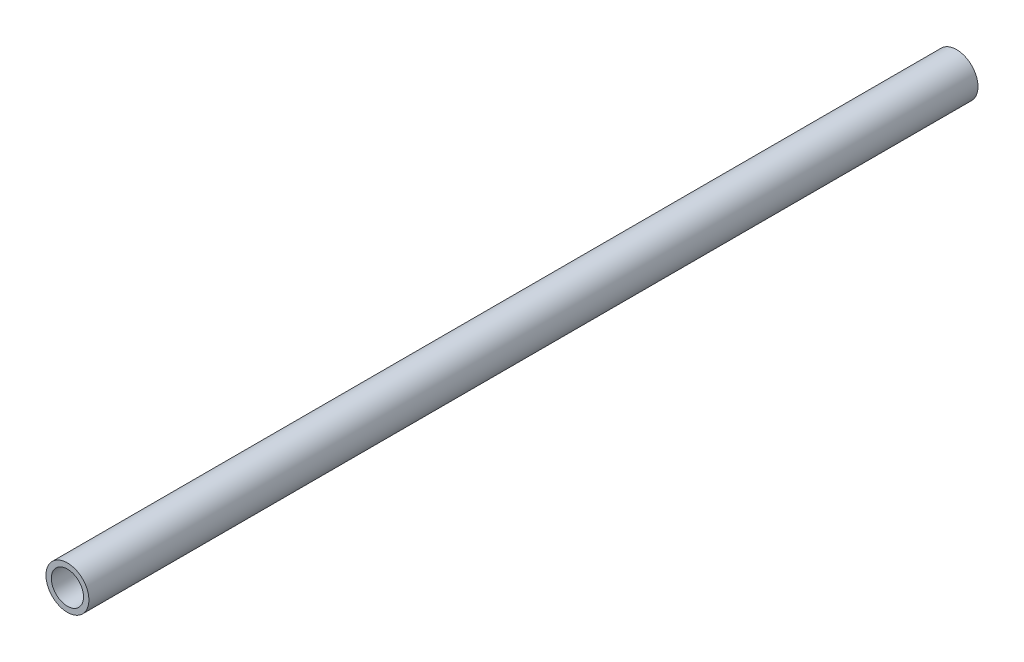
SolidWorks part; units mm, degrees
material "PC High Viscosity"
ref_plane "Front Plane" through (0, 0, 0) normal (0, 0, 1) x (1, 0, 0)
ref_plane "Top Plane" through (0, 0, 0) normal (0, 1, 0) x (1, 0, 0)
ref_plane "Right Plane" through (0, 0, 0) normal (1, 0, 0) x (0, 0, -1)
sketch "Sketch2" plane through (0, 0, 0) normal (0, 0, 1) x (1, 0, 0)
  circle A0 centre (0, 0) radius 9.525
  circle A1 centre (0, 0) radius 12.7
  dimension "D1" = 25.4
  dimension "D2" = 19.05
extrude "Boss-Extrude1" add sketch "Sketch2" along normal mid plane 526.1381
